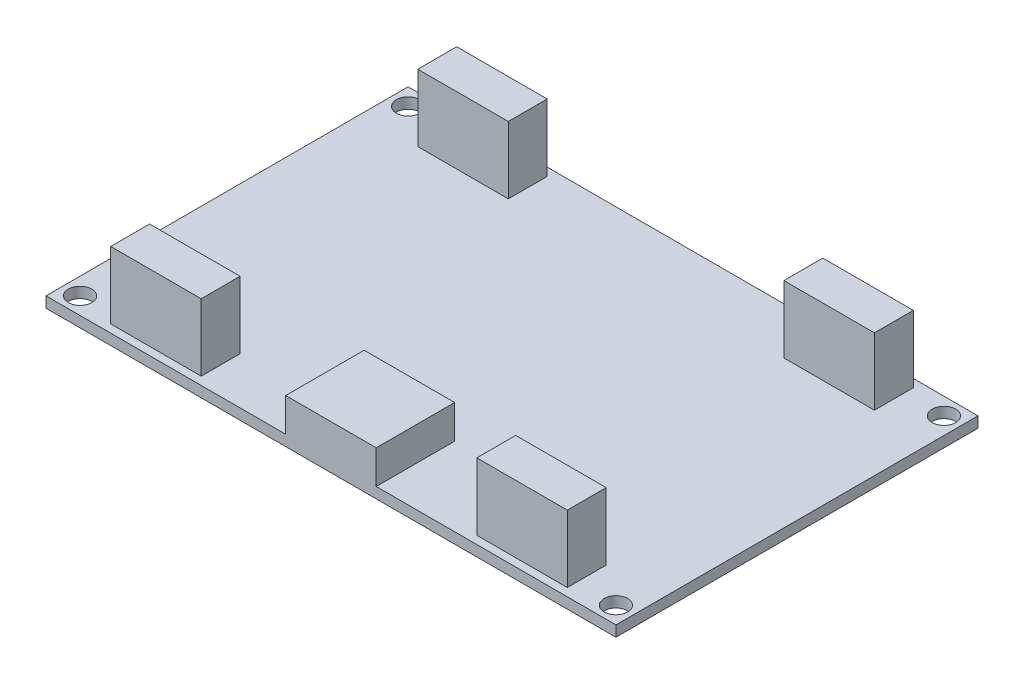
SolidWorks part; units mm, degrees
material "ABS"
ref_plane "Front" through (0, 0, 0) normal (0, 0, 1) x (1, 0, 0)
ref_plane "Top" through (0, 0, 0) normal (0, 1, 0) x (1, 0, 0)
ref_plane "Right" through (0, 0, 0) normal (1, 0, 0) x (0, 0, -1)
sketch "Sketch7" plane through (0, 0, 0) normal (0, 1, 0) x (1, 0, 0)
  line L1 (0, 0) -> (85, 0)
  line L2 (0, 0) -> (0, 54)
  line L3 (0, 54) -> (85, 54)
  line L4 (85, 0) -> (85, 54)
  dimension "D1" = 54
  dimension "D2" = 85
extrude "Boss-Extrude2" add sketch "Sketch7" along normal blind 1.6
hole_wizard "Ø3.5 (3.5) Diameter Hole1" positions "Sketch13" profile "Sketch12" hole size "Ø3.5" standard "Ansi Metric" end condition through all
sketch "Sketch13" plane through (0, 1.6, 0) normal (0, 1, 0) x (-1, 0, 0)
  line L0 (0, -54) -> (0, 0) construction
  line L1 (-85, -54) -> (0, -54) construction
  line L2 (0, 0) -> (-85, 0) construction
  line L3 (-85, 0) -> (-85, -54) construction
  point P0 (-2.54, -2.54)
  point P2 (-2.54, -51.46)
  point P4 (-82.46, -51.46)
  point P6 (-82.46, -2.54)
  dimension "D1" = 2.54
  dimension "D2" = 2.54
  dimension "D3" = 2.54
  dimension "D4" = 2.54
  dimension "D5" = 2.54
  dimension "D6" = 2.54
  dimension "D7" = 2.54
  dimension "D8" = 2.54
sketch "Sketch12" plane through (2.54, 1.6, -2.54) normal (1, 0, 0) x (0, 0, 1)
  line L0 (0, 0) -> (0, 1.6)
  line L1 (0, 1.6) -> (1.75, 1.6)
  line L2 (1.75, 1.6) -> (1.75, 0)
  line L5 (1.75, 0) -> (0, 0)
  line L11 (0, -6.35) -> (0, 107.95) construction
  dimension "Thru Hole Dia." = 3.5
  dimension "Thru Hole Depth" = 1.6
sketch "Sketch14" plane through (0, 1.6, 0) normal (0, 1, 0) x (1, 0, 0)
  line L0 (85, 54) -> (0, 54) construction
  line L1 (8.45, 52.8) -> (21.95, 52.8)
  line L2 (8.45, 52.8) -> (8.45, 47)
  line L3 (8.45, 47) -> (21.95, 47)
  line L4 (21.95, 52.8) -> (21.95, 47)
  line L5 (8.45, 52.8) -> (21.95, 47) construction
  line L6 (8.45, 47) -> (21.95, 52.8) construction
  line L7 (0, 54) -> (0, 0) construction
  point P0 (15.2, 49.9)
  dimension "D1" = 5.8
  dimension "D2" = 13.5
  dimension "D3" = 4.1
  dimension "D4" = 15.2
extrude "Boss-Extrude3" add sketch "Sketch14" along normal blind 10
pattern_linear "LPattern1" count 2 spacing 54.6 along (1, 0, 0) count 2 spacing 45.8 along (0, 0, 1) of "Boss-Extrude3"
sketch "Sketch15" plane through (0, 1.6, 0) normal (0, 1, 0) x (1, 0, 0)
  line L0 (0, 0) -> (85, 0) construction
  line L1 (35.75, 11.7) -> (49.25, 11.7)
  line L2 (35.75, 11.7) -> (35.75, 0)
  line L3 (35.75, 0) -> (49.25, 0)
  line L4 (49.25, 11.7) -> (49.25, 0)
  line L5 (35.75, 11.7) -> (49.25, 0) construction
  line L6 (35.75, 0) -> (49.25, 11.7) construction
  line L7 (85, 0) -> (85, 54) construction
  point P0 (42.5, 5.85)
  dimension "D1" = 11.7
  dimension "D2" = 13.5
  dimension "D3" = 5.85
  dimension "D4" = 42.5
extrude "Boss-Extrude4" add sketch "Sketch15" along normal blind 5
